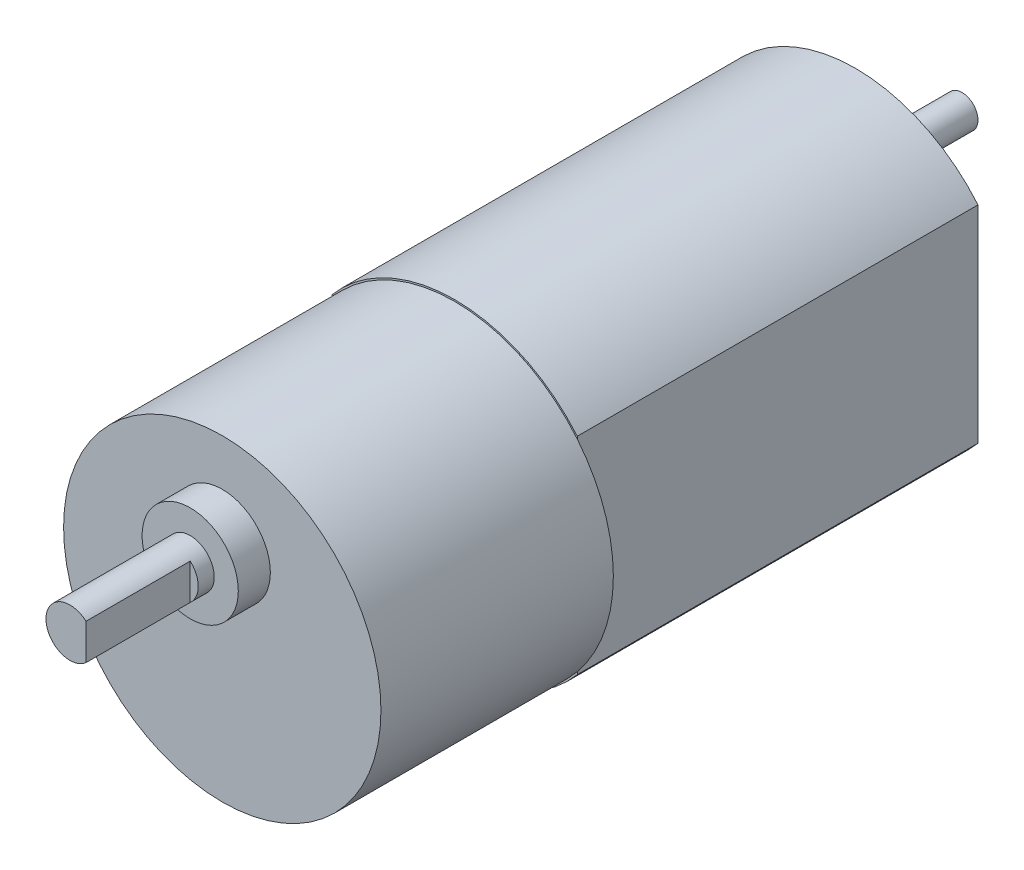
SolidWorks part; units mm, degrees
ref_plane "Plan de face" through (0, 0, 0) normal (0, 0, 1) x (1, 0, 0)
ref_plane "Plan de dessus" through (0, 0, 0) normal (0, 1, 0) x (1, 0, 0)
ref_plane "Plan de droite" through (0, 0, 0) normal (1, 0, 0) x (0, 0, -1)
sketch "Sketch1" plane through (0, 0, 0) normal (0, 0, 1) x (1, 0, 0)
  line L0 (-7.65, 6.4403) -> (-7.65, -6.4403)
  line L1 (-7.65, -6.4403) -> (7.65, -6.4403) construction
  line L2 (7.65, -6.4403) -> (7.65, 6.4403)
  line L3 (7.65, 6.4403) -> (-7.65, 6.4403) construction
  arc A0 (-7.65, -6.4403) -> (7.65, -6.4403) centre (0, 0) ccw
  arc A1 (7.65, 6.4403) -> (-7.65, 6.4403) centre (0, 0) ccw
  dimension "D1" = 20
  dimension "D2" = 15.3
extrude "Extrude1" add sketch "Sketch1" along normal blind 25
sketch "Sketch2" plane through (0, 0, 25) normal (0, 0, 1) x (1, 0, 0)
  circle A0 centre (0, 0) radius 9.9
  dimension "D1" = 19.8
extrude "Extrude2" add sketch "Sketch2" along normal blind 14.5
sketch "Sketch3" plane through (0, 0, 0) normal (0, 0, -1) x (-1, 0, 0)
  circle A0 centre (0, 0) radius 3
  dimension "D1" = 6
extrude "Extrude3" add sketch "Sketch3" along normal blind 2.5
sketch "Sketch4" plane through (0, 0, -2.5) normal (0, 0, -1) x (-1, 0, 0)
  circle A0 centre (0, 0) radius 1
  dimension "D1" = 2
extrude "Extrude4" add sketch "Sketch4" along normal blind 3
sketch "Sketch5" plane through (0, 0, 0) normal (0, 0, -1) x (-1, 0, 0)
  line L0 (-2.65, 7.0162) -> (2.65, -7.0162) construction
  line L1 (-7.65, -6.2839) -> (-7.65, 6.2839) construction
  circle A0 centre (-2.65, 7.0162) radius 1
  circle A1 centre (2.65, -7.0162) radius 1
  dimension "D2" = 2
  dimension "D3" = 5
  dimension "D1" = 15
extrude "Extrude5" add sketch "Sketch5" along normal blind 4
sketch "Sketch6" plane through (0, 0, 39.5) normal (0, 0, 1) x (1, 0, 0)
  circle A0 centre (0, 4) radius 3
  dimension "D1" = 6
  dimension "D2" = 4
extrude "Extrude6" add sketch "Sketch6" along normal blind 2
sketch "Sketch7" plane through (0, 0, 41.5) normal (0, 0, 1) x (1, 0, 0)
  circle A0 centre (0, 4) radius 1.5
  dimension "D1" = 3
extrude "Extrude7" add sketch "Sketch7" along normal blind 7.5
sketch "Sketch8" plane through (0, 0, 49) normal (0, 0, 1) x (1, 0, 0)
  line L1 (1, 5.118) -> (1.5, 5.118)
  line L2 (1, 5.118) -> (1, 2.882)
  line L3 (1, 2.882) -> (1.5, 2.882)
  line L4 (1.5, 5.118) -> (1.5, 2.882)
  circle A0 centre (0, 4) radius 1.5 construction
  circle A1 centre (0, 4) radius 1.5 construction
  dimension "D1" = 0.5
extrude "Extrude8" cut sketch "Sketch8" against normal blind 6.5
